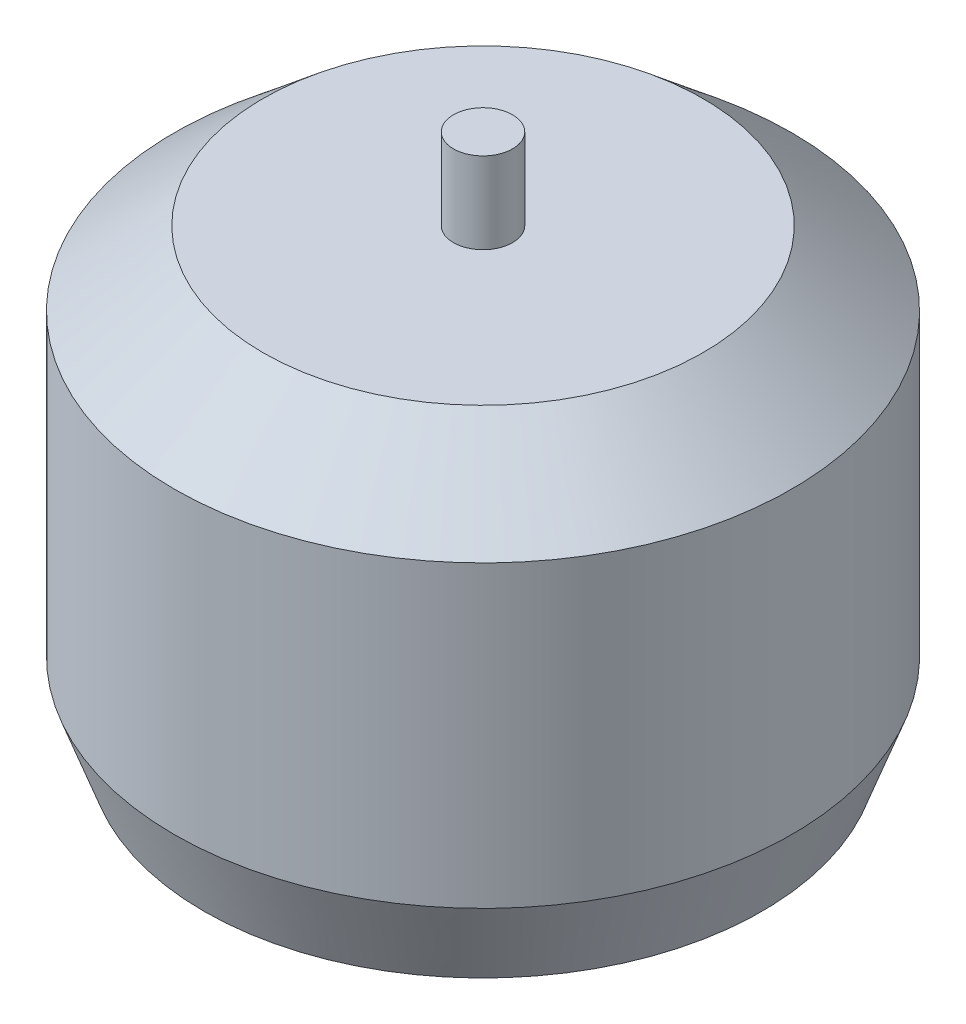
SolidWorks part; units mm, degrees
ref_plane "Front Plane" through (0, 0, 0) normal (0, 0, 1) x (1, 0, 0)
ref_plane "Top Plane" through (0, 0, 0) normal (0, 1, 0) x (1, 0, 0)
ref_plane "Right Plane" through (0, 0, 0) normal (1, 0, 0) x (0, 0, -1)
sketch "Sketch1" plane through (0, 0, 0) normal (0, 1, 0) x (1, 0, 0)
  circle A0 centre (-5.6491, -5.3281) radius 20.9
  dimension "D1" = 41.8
extrude "Boss-Extrude1" add sketch "Sketch1" along normal blind 30.75
chamfer "Chamfer1" distance 5 distance2 6 1 edges at (-5.6491, 30.75, 26.2281)
chamfer "Chamfer2" distance 2 angle 70 1 edges at (-5.6491, 0, 26.2281)
sketch "Sketch2" plane through (0, 30.75, 0) normal (0, 1, 0) x (1, 0, 0)
  circle A0 centre (-5.6491, -5.3281) radius 2
  circle A1 centre (-5.6491, -5.3281) radius 14.9 construction
  dimension "D1" = 4
  dimension "D2" = 0
  dimension "D3" = 0
extrude "Boss-Extrude2" add sketch "Sketch2" along normal blind 5.5
sketch "Sketch3" plane through (0, 0, 0) normal (0, -1, 0) x (1, 0, 0)
  circle A0 centre (-5.6491, 5.3281) radius 4
  circle A1 centre (-5.6491, 5.3281) radius 18.9 construction
  dimension "D1" = 8
  dimension "D2" = 0
extrude "Boss-Extrude3" add sketch "Sketch3" along normal blind 2.55 contours A0
sketch "Sketch4" plane through (0, 0, 0) normal (0, -1, 0) x (1, 0, 0)
  circle A0 centre (-5.9087, 17.486) radius 4
  point P2 (-5.9087, 17.486)
  dimension "D1" = 8
